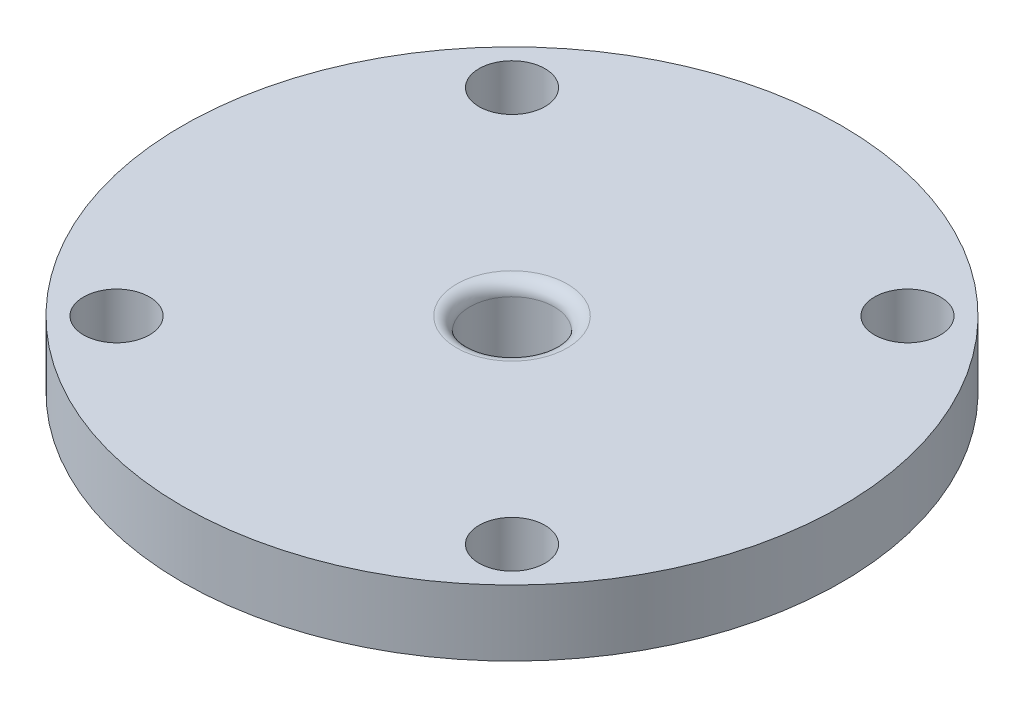
SolidWorks part; units mm, degrees
ref_plane "Front Plane" through (0, 0, 0) normal (0, 0, 1) x (1, 0, 0)
ref_plane "Top Plane" through (0, 0, 0) normal (0, 1, 0) x (1, 0, 0)
ref_plane "Right Plane" through (0, 0, 0) normal (1, 0, 0) x (0, 0, -1)
sketch "Sketch1" plane through (0, 0, 0) normal (0, 1, 0) x (1, 0, 0)
  circle A0 centre (0, 0) radius 25
  dimension "D1" = 50
extrude "Boss-Extrude1" add sketch "Sketch1" along normal blind 5
sketch "Sketch2" plane through (0, 5, 0) normal (0, 1, 0) x (1, 0, 0)
  line L4 (-15, -15) -> (15, -15) construction
  line L5 (-15, -15) -> (-15, 15) construction
  line L6 (-15, 15) -> (15, 15) construction
  line L7 (15, -15) -> (15, 15) construction
  line L8 (-15, -15) -> (15, 15) construction
  line L9 (-15, 15) -> (15, -15) construction
  circle A0 centre (-15, 15) radius 2.5
  circle A1 centre (15, 15) radius 2.5
  circle A2 centre (15, -15) radius 2.5
  circle A3 centre (-15, -15) radius 2.5
  point P6 (0, 0)
  point P21 (0, 0)
  dimension "D3" = 5
  dimension "D1" = 30
  dimension "D4" = 4
extrude "Cut-Extrude1" cut sketch "Sketch2" against normal through all
sketch "Sketch3" plane through (0, 5, 0) normal (0, 1, 0) x (1, 0, 0)
  circle A0 centre (0, 0) radius 3.2
  dimension "D1" = 6.4
extrude "Cut-Extrude2" cut sketch "Sketch3" against normal through all
fillet "Fillet1" radius 1 1 edges at (0, 5, 3.2)
